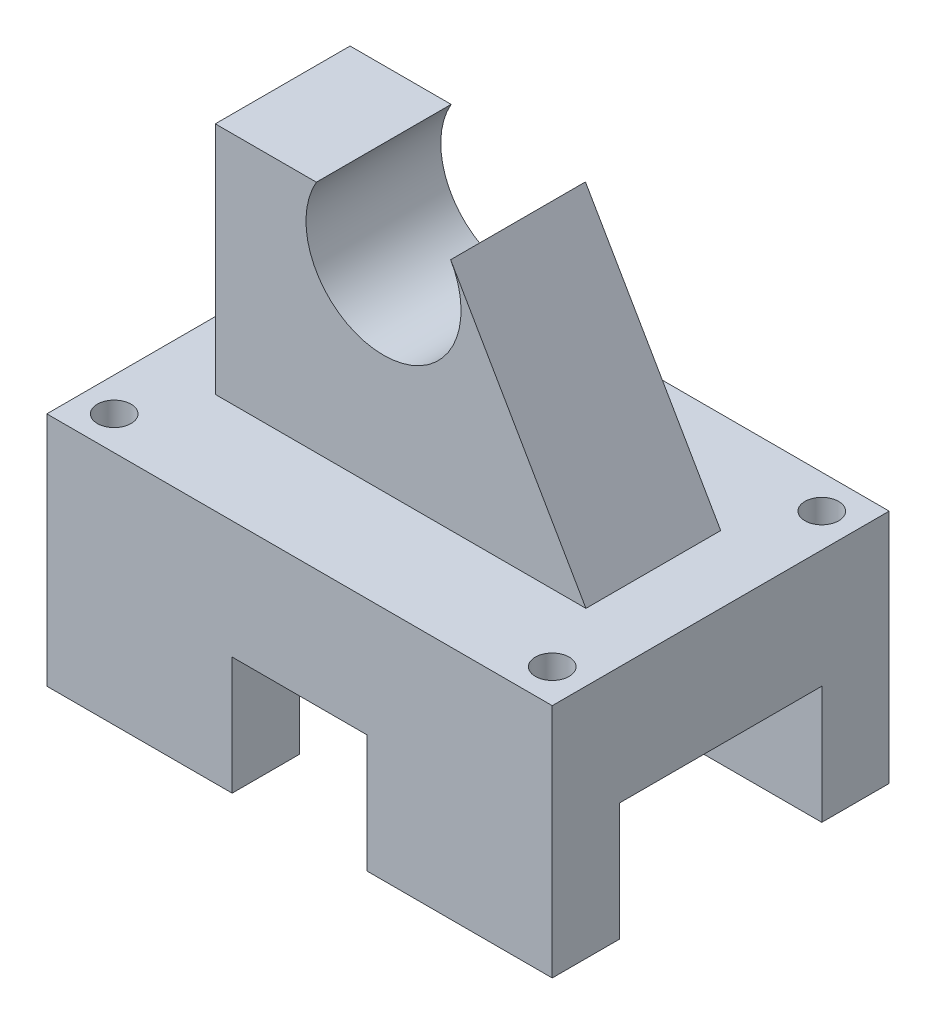
SolidWorks part; units mm, degrees
ref_plane "Front Plane" through (0, 0, 0) normal (0, 0, 1) x (1, 0, 0)
ref_plane "Top Plane" through (0, 0, 0) normal (0, 1, 0) x (1, 0, 0)
ref_plane "Right Plane" through (0, 0, 0) normal (1, 0, 0) x (0, 0, -1)
sketch "Sketch1" plane through (0, 0, 0) normal (0, 0, 1) x (1, 0, 0)
  line L1 (-75, 35) -> (75, 35)
  line L2 (-75, 35) -> (-75, -35)
  line L3 (-75, -35) -> (75, -35)
  line L4 (75, 35) -> (75, -35)
  line L5 (-75, 35) -> (75, -35) construction
  line L6 (-75, -35) -> (75, 35) construction
  point P0 (0, 0)
  dimension "D1" = 70
  dimension "D2" = 150
extrude "Boss-Extrude1" add sketch "Sketch1" along normal blind 100
sketch "Sketch2" plane through (0, 0, 100) normal (0, 0, 1) x (1, 0, 0)
  line L0 (-20, 0) -> (-20, -35) construction
  line L2 (-20, 0) -> (20, 0) construction
  line L3 (-75, -35) -> (75, -35) construction
  line L4 (-20, -35) -> (20, -35) construction
  line L5 (20, 0) -> (20, -35)
  line L6 (20, -35) -> (-20, -35)
  line L7 (-20, -35) -> (-20, 0)
  line L8 (-20, 0) -> (20, 0)
extrude "Cut-Extrude1" cut sketch "Sketch2" against normal blind 100
sketch "Sketch3" plane through (75, 0, 0) normal (1, 0, 0) x (0, 0, -1)
  line L0 (-80, -35) -> (-20, -35)
  line L1 (-100, -35) -> (0, -35) construction
  line L2 (-80, 0) -> (-20, 0)
  line L3 (-20, 0) -> (-20, -35)
  line L4 (-80, 0) -> (-80, -35)
extrude "Cut-Extrude2" cut sketch "Sketch3" against normal blind 150
sketch "Sketch4" plane through (0, 35, 0) normal (0, 1, 0) x (1, 0, 0)
  line L2 (75, -70) -> (-75, -70)
  line L3 (55, -70) -> (-55, -70)
  line L5 (75, -30) -> (-75, -30)
  line L6 (55, -30) -> (-55, -30)
  line L8 (55, -100) -> (55, 0)
  line L9 (55, -70) -> (55, -30)
  line L11 (-55, -100) -> (-55, 0)
  line L12 (-55, -70) -> (-55, -30)
  dimension "D1" = 30
  dimension "D2" = 30
  dimension "D3" = 20
  dimension "D4" = 20
ref_plane "Plane1" through (0, 0, 50) normal (0, 0, 1) x (1, 0, 0)
sketch "Sketch5" plane through (0, 0, 50) normal (0, 0, 1) x (1, 0, 0)
  line L0 (55, 35) -> (14.8501, 104.5416)
  line L4 (55, 35) -> (-55, 35) construction
  line L5 (75, 35) -> (-75, 35) construction
  line L6 (55, 35) -> (-55, 35)
  line L7 (-55, 35) -> (-55, 104.5416)
  line L8 (-55, 104.5416) -> (-25, 104.5416)
  arc A0 (14.8501, 104.5416) -> (-25, 104.5416) centre (-5.0749, 93.0379) cw
  dimension "D1" = 60
  dimension "D2" = 30
extrude "Boss-Extrude2" add sketch "Sketch5" along normal blind 20 and the other way blind 20
sketch "Sketch11" plane through (0, 35, 0) normal (0, 1, 0) x (1, 0, 0)
  circle A0 centre (65, -10) radius 5
  circle A1 centre (-65, -10) radius 5
  circle A2 centre (-65, -90) radius 5
  circle A3 centre (65, -90) radius 5
  dimension "D3" = 2
  dimension "D4" = 2
extrude "Cut-Extrude4" cut sketch "Sketch11" against normal blind 50
